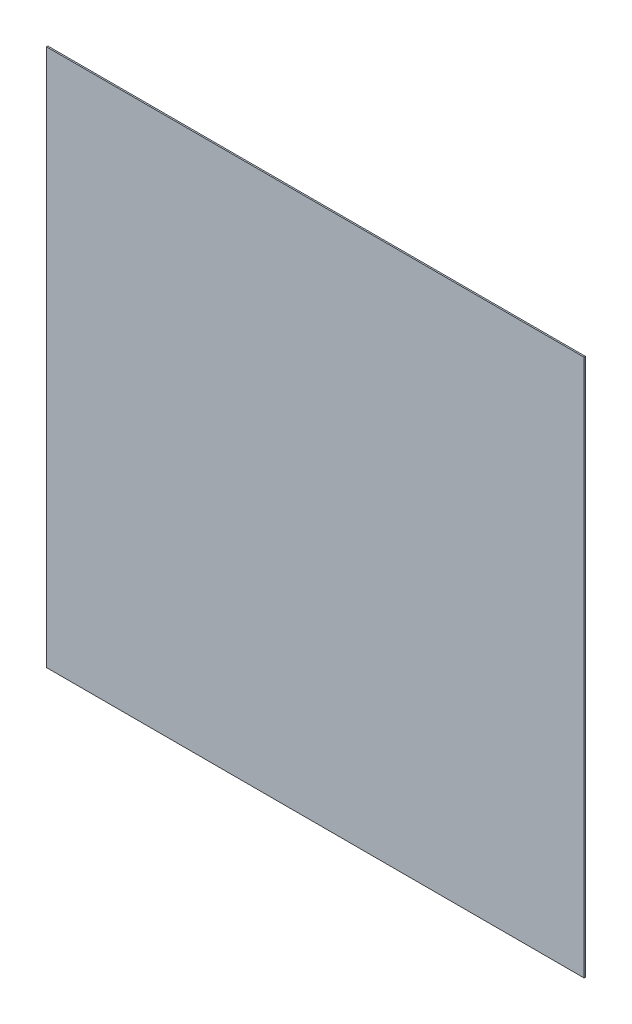
SolidWorks part; units mm, degrees
ref_plane "Front Plane" through (0, 0, 0) normal (0, 0, 1) x (1, 0, 0)
ref_plane "Top Plane" through (0, 0, 0) normal (0, 1, 0) x (1, 0, 0)
ref_plane "Right Plane" through (0, 0, 0) normal (1, 0, 0) x (0, 0, -1)
sketch "Sketch1" plane through (0, 0, 0) normal (0, 0, 1) x (1, 0, 0)
  line L1 (-609.6, 609.6) -> (609.6, 609.6)
  line L2 (-609.6, 609.6) -> (-609.6, -609.6)
  line L3 (-609.6, -609.6) -> (609.6, -609.6)
  line L4 (609.6, 609.6) -> (609.6, -609.6)
  line L5 (-609.6, 609.6) -> (609.6, -609.6) construction
  line L6 (-609.6, -609.6) -> (609.6, 609.6) construction
  point P0 (0, 0)
  dimension "D1" = 1219.2
  dimension "D2" = 1219.2
extrude "Boss-Extrude1" add sketch "Sketch1" along normal blind 3.175
